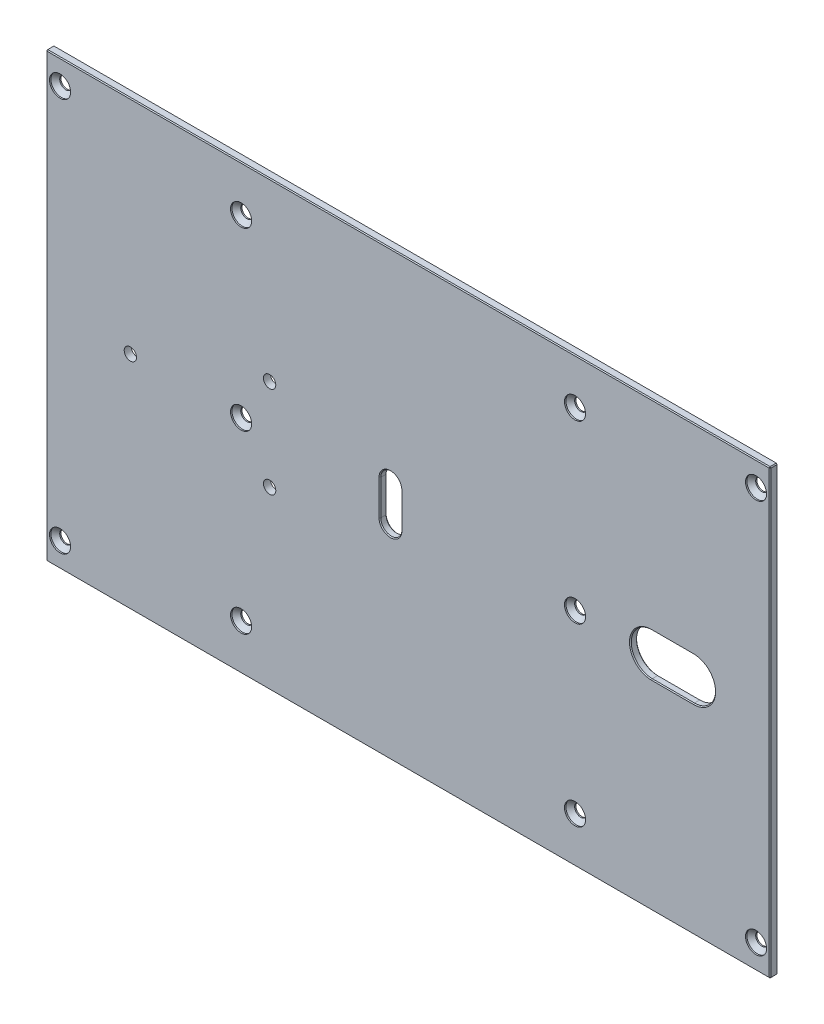
SolidWorks part; units mm, degrees
ref_plane "Front Plane" through (0, 0, 0) normal (0, 0, 1) x (1, 0, 0)
ref_plane "Top Plane" through (0, 0, 0) normal (0, 1, 0) x (1, 0, 0)
ref_plane "Right Plane" through (0, 0, 0) normal (1, 0, 0) x (0, 0, -1)
sketch "Sketch1" plane through (0, 0, 0) normal (0, 0, 1) x (1, 0, 0)
  line L0 (176.75, 3) -> (-28.75, 3) construction
  line L1 (-29, 3) -> (177, 3)
  line L2 (-29, 3) -> (-29, -123)
  line L3 (-29, -123) -> (177, -123)
  line L4 (177, 3) -> (177, -123)
  line L5 (-29, 2.75) -> (-29, 0) construction
  line L6 (177, -122.75) -> (177, -120) construction
  line L7 (176.75, -123) -> (-28.75, -123) construction
  circle A0 centre (-25, -4) radius 1.75
  circle A1 centre (26.5, -10) radius 1.75
  circle A2 centre (121.5, -10) radius 1.75
  circle A3 centre (173, -4) radius 1.75
  circle A4 centre (173, -116) radius 1.75
  circle A5 centre (121.5, -60) radius 1.75
  circle A6 centre (121.5, -110) radius 1.75
  circle A7 centre (26.5, -110) radius 1.75
  circle A8 centre (26.5, -60) radius 1.75
  circle A9 centre (-25, -116) radius 1.75
  dimension "D1" = 3.5
extrude "Boss-Extrude1" add sketch "Sketch1" along normal blind 2
sketch "Sketch2" plane through (0, 0, 2) normal (0, 0, 1) x (1, 0, 0)
  circle A0 centre (34.6218, -47) radius 1.75
  circle A1 centre (34.6218, -73) radius 1.75
  circle A2 centre (-5, -60) radius 1.75
  dimension "D1" = 3.5
extrude "Cut-Extrude1" cut sketch "Sketch2" against normal up to next
sketch "Sketch7" plane through (0, 0, 2) normal (0, 0, 1) x (1, 0, 0)
  line L0 (-29, -60) -> (177, -60) construction
  line L1 (-29, 3) -> (-29, -123) construction
  line L2 (177, -123) -> (177, 3) construction
  line L3 (74, 3) -> (74, -123) construction
  line L4 (177, 3) -> (-29, 3) construction
  line L5 (-29, -123) -> (177, -123) construction
  line L6 (69, -55) -> (69, -65) construction
  line L7 (72, -55) -> (72, -65)
  line L8 (66, -55) -> (66, -65)
  line L9 (143.25, -60) -> (155.25, -60) construction
  line L12 (121.5, -110) -> (177, -110) construction
  line L14 (149.25, -110) -> (149.25, 3) construction
  line L15 (143.25, -54) -> (155.25, -54)
  line L16 (143.25, -66) -> (155.25, -66)
  arc A0 (72, -55) -> (66, -55) centre (69, -55) ccw
  arc A1 (66, -65) -> (72, -65) centre (69, -65) ccw
  arc A4 (143.25, -54) -> (143.25, -66) centre (143.25, -60) ccw
  arc A5 (155.25, -66) -> (155.25, -54) centre (155.25, -60) ccw
  point P14 (69, -60)
  point P21 (149.25, -60)
  point P29 (149.25, -110)
  dimension "D2" = 6
  dimension "D1" = 95
  dimension "D3" = 10
  dimension "D4" = 12
  dimension "D5" = 12
extrude "Cut-Extrude2" cut sketch "Sketch7" against normal up to next
hole_wizard "CSK for M3 Flat Head Machine Screw1" positions "Sketch3" profile "Sketch4" countersink size "M3" standard "ANSI Metric" end condition through all
sketch "Sketch3" plane through (0, 0, 2) normal (0, 0, 1) x (1, 0, 0)
  point P0 (-25, -4)
  point P3 (26.5, -10)
  point P6 (26.5, -60)
  point P9 (26.5, -110)
  point P12 (-25, -116)
  point P15 (121.5, -10)
  point P18 (173, -4)
  point P21 (173, -116)
  point P24 (121.5, -60)
  point P27 (121.5, -110)
sketch "Sketch4" plane through (-25, -4, 2) normal (1, 0, 0) x (0, -1, 0)
  line L0 (0, 0) -> (0, 2)
  line L1 (0, 2) -> (1.75, 2)
  line L2 (1.75, 2) -> (1.75, 1.65)
  line L3 (1.75, 1.65) -> (3, 0.4)
  line L4 (3, 0.4) -> (3, 0)
  line L6 (3, 0) -> (0, 0)
  line L7 (-1.75, 1.65) -> (-3, 0.4) construction
  line L11 (0, -6.35) -> (0, 107.95) construction
  dimension "Thru Hole Dia." = 3.5
  dimension "Thru Hole Depth" = 2
  dimension "C'Sink Dia." = 6
  dimension "C'Sink Angle" = 90
  dimension "Head Clearance" = 0.4
chamfer "Chamfer1" distance 0.25 angle 45 24 edges at (66, -60, 0) (69, -52, 0) (69, -68, 0) (72, -60, 0) (66, -60, 2) (69, -68, 2) (69, -52, 2) (72, -60, 2) (74, 3, 2) (177, 3, 1) (177, -60, 2) (-29, 3, 1) (-29, -60, 2) (177, -123, 1) (74, -123, 2) (-29, -123, 1) (149.25, -66, 0) (137.25, -60, 0) (161.25, -60, 0) (149.25, -54, 0) (149.25, -66, 2) (161.25, -60, 2) (137.25, -60, 2) (149.25, -54, 2)
sketch "Sketch8" [suppressed] plane through (0, 0, 0) normal (0, 0, -1) x (-1, 0, 0)
  line L0 (-31.2468, -44.0411) -> (-33.7468, -42.5977)
  line L1 (-34.4968, -50.1033) -> (-31.9968, -48.6599)
  line L2 (-31.8718, -48.4434) -> (-31.8718, -45.5566)
  line L3 (-31.9968, -45.3401) -> (-34.4968, -43.8967)
  line L4 (-34.7468, -43.8967) -> (-37.2468, -45.3401)
  line L5 (-37.3718, -45.5566) -> (-37.3718, -48.4434)
  line L6 (-37.2468, -48.6599) -> (-34.7468, -50.1033)
  line L7 (-34.4968, -76.1033) -> (-31.9968, -74.6599)
  line L8 (-31.8718, -74.4434) -> (-31.8718, -71.5566)
  line L9 (-31.9968, -71.3401) -> (-34.4968, -69.8967)
  line L10 (-34.7468, -69.8967) -> (-37.2468, -71.3401)
  line L11 (-37.3718, -71.5566) -> (-37.3718, -74.4434)
  line L12 (-37.2468, -74.6599) -> (-34.7468, -76.1033)
  line L13 (5.125, -63.1033) -> (7.625, -61.6599)
  line L14 (7.75, -61.4434) -> (7.75, -58.5566)
  line L15 (7.625, -58.3401) -> (5.125, -56.8967)
  line L16 (4.875, -56.8967) -> (2.375, -58.3401)
  line L17 (2.25, -58.5566) -> (2.25, -61.4434)
  line L18 (2.375, -61.6599) -> (4.875, -63.1033)
  line L19 (-35.4968, -42.5977) -> (-37.9968, -44.0411)
  line L20 (-38.8718, -45.5566) -> (-38.8718, -48.4434)
  line L21 (-37.9968, -49.9589) -> (-35.4968, -51.4023)
  line L22 (-33.7468, -51.4023) -> (-31.2468, -49.9589)
  line L23 (-30.3718, -48.4434) -> (-30.3718, -45.5566)
  line L24 (-30.3718, -74.4434) -> (-30.3718, -71.5566)
  line L25 (-31.2468, -70.0411) -> (-33.7468, -68.5977)
  line L26 (-35.4968, -68.5977) -> (-37.9968, -70.0411)
  line L27 (-38.8718, -71.5566) -> (-38.8718, -74.4434)
  line L28 (-37.9968, -75.9589) -> (-35.4968, -77.4023)
  line L29 (-33.7468, -77.4023) -> (-31.2468, -75.9589)
  line L30 (8.375, -57.0411) -> (5.875, -55.5977)
  line L31 (4.125, -55.5977) -> (1.625, -57.0411)
  line L32 (0.75, -58.5566) -> (0.75, -61.4434)
  line L33 (1.625, -62.9589) -> (4.125, -64.4023)
  line L34 (5.875, -64.4023) -> (8.375, -62.9589)
  line L35 (9.25, -61.4434) -> (9.25, -58.5566)
  circle A0 centre (-34.6218, -47) radius 2.75 construction
  circle A1 centre (-34.6218, -73) radius 2.75 construction
  circle A2 centre (5, -60) radius 2.75 construction
  arc A3 (2.375, -58.3401) -> (2.25, -58.5566) centre (2.5, -58.5566) ccw
  arc A4 (2.25, -61.4434) -> (2.375, -61.6599) centre (2.5, -61.4434) ccw
  arc A5 (5.125, -63.1033) -> (4.875, -63.1033) centre (5, -62.8868) cw
  arc A6 (7.625, -61.6599) -> (7.75, -61.4434) centre (7.5, -61.4434) ccw
  arc A7 (7.75, -58.5566) -> (7.625, -58.3401) centre (7.5, -58.5566) ccw
  arc A8 (5.125, -56.8967) -> (4.875, -56.8967) centre (5, -57.1132) ccw
  arc A9 (-37.3718, -74.4434) -> (-37.2468, -74.6599) centre (-37.1218, -74.4434) ccw
  arc A10 (-34.4968, -76.1033) -> (-34.7468, -76.1033) centre (-34.6218, -75.8868) cw
  arc A11 (-31.9968, -74.6599) -> (-31.8718, -74.4434) centre (-32.1218, -74.4434) ccw
  arc A12 (-31.8718, -71.5566) -> (-31.9968, -71.3401) centre (-32.1218, -71.5566) ccw
  arc A13 (-34.4968, -69.8967) -> (-34.7468, -69.8967) centre (-34.6218, -70.1132) ccw
  arc A14 (-37.2468, -71.3401) -> (-37.3718, -71.5566) centre (-37.1218, -71.5566) ccw
  arc A15 (-37.2468, -45.3401) -> (-37.3718, -45.5566) centre (-37.1218, -45.5566) ccw
  arc A16 (-37.3718, -48.4434) -> (-37.2468, -48.6599) centre (-37.1218, -48.4434) ccw
  arc A17 (-34.4968, -50.1033) -> (-34.7468, -50.1033) centre (-34.6218, -49.8868) cw
  arc A18 (-31.9968, -48.6599) -> (-31.8718, -48.4434) centre (-32.1218, -48.4434) ccw
  arc A19 (-31.8718, -45.5566) -> (-31.9968, -45.3401) centre (-32.1218, -45.5566) ccw
  arc A20 (-34.4968, -43.8967) -> (-34.7468, -43.8967) centre (-34.6218, -44.1132) ccw
  arc A21 (-33.7468, -42.5977) -> (-35.4968, -42.5977) centre (-34.6218, -44.1132) ccw
  arc A22 (-37.9968, -44.0411) -> (-38.8718, -45.5566) centre (-37.1218, -45.5566) ccw
  arc A23 (-38.8718, -48.4434) -> (-37.9968, -49.9589) centre (-37.1218, -48.4434) ccw
  arc A24 (-33.7468, -51.4023) -> (-35.4968, -51.4023) centre (-34.6218, -49.8868) cw
  arc A25 (-31.2468, -49.9589) -> (-30.3718, -48.4434) centre (-32.1218, -48.4434) ccw
  arc A26 (-30.3718, -45.5566) -> (-31.2468, -44.0411) centre (-32.1218, -45.5566) ccw
  arc A27 (-30.3718, -71.5566) -> (-31.2468, -70.0411) centre (-32.1218, -71.5566) ccw
  arc A28 (-33.7468, -68.5977) -> (-35.4968, -68.5977) centre (-34.6218, -70.1132) ccw
  arc A29 (-37.9968, -70.0411) -> (-38.8718, -71.5566) centre (-37.1218, -71.5566) ccw
  arc A30 (-38.8718, -74.4434) -> (-37.9968, -75.9589) centre (-37.1218, -74.4434) ccw
  arc A31 (-33.7468, -77.4023) -> (-35.4968, -77.4023) centre (-34.6218, -75.8868) cw
  arc A32 (-31.2468, -75.9589) -> (-30.3718, -74.4434) centre (-32.1218, -74.4434) ccw
  arc A33 (5.875, -55.5977) -> (4.125, -55.5977) centre (5, -57.1132) ccw
  arc A34 (1.625, -57.0411) -> (0.75, -58.5566) centre (2.5, -58.5566) ccw
  arc A35 (0.75, -61.4434) -> (1.625, -62.9589) centre (2.5, -61.4434) ccw
  arc A36 (5.875, -64.4023) -> (4.125, -64.4023) centre (5, -62.8868) cw
  arc A37 (8.375, -62.9589) -> (9.25, -61.4434) centre (7.5, -61.4434) ccw
  arc A38 (9.25, -58.5566) -> (8.375, -57.0411) centre (7.5, -58.5566) ccw
  dimension "D2" = 0.25
  dimension "D1" = 5.5
  dimension "D3" = 1.5
  dimension "D4" = 1.5
  dimension "D5" = 1.5
extrude "Boss-Extrude2" [suppressed] add sketch "Sketch8" along normal blind 2
fillet "Fillet1" [suppressed] radius 1
chamfer "Chamfer2" [suppressed] distance 0.25 angle 45
